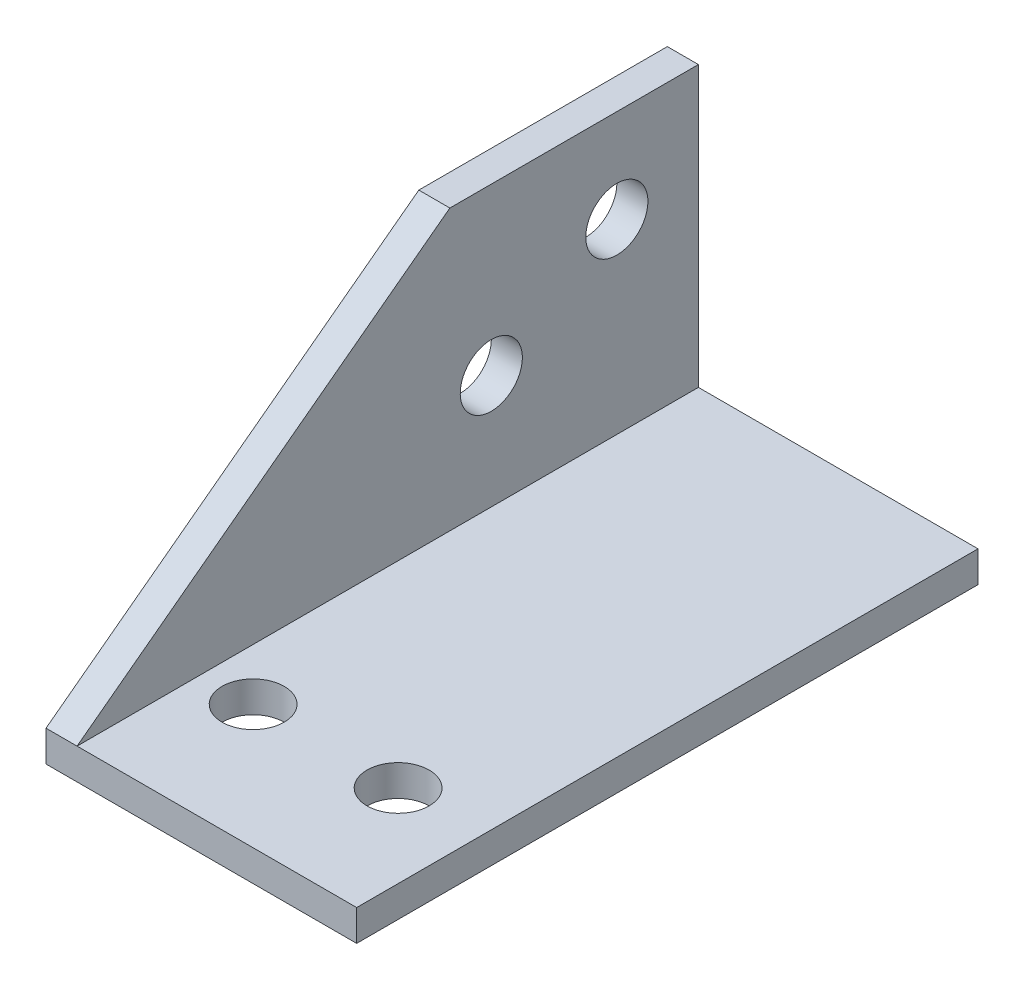
SolidWorks part; units mm, degrees
ref_plane "Plan de face" through (0, 0, 0) normal (0, 0, 1) x (1, 0, 0)
ref_plane "Plan de dessus" through (0, 0, 0) normal (0, 1, 0) x (1, 0, 0)
ref_plane "Plan de droite" through (0, 0, 0) normal (1, 0, 0) x (0, 0, -1)
sketch "Esquisse1" plane through (0, 0, 0) normal (0, 0, 1) x (1, 0, 0)
  line L0 (-13.9999, 0.6824) -> (-15.4999, 0.6824)
  line L1 (-15.4999, 0.6824) -> (-15.4999, -14.3176)
  line L2 (-15.4999, -14.3176) -> (-0.4999, -14.3176)
  line L3 (-0.4999, -14.3176) -> (-0.4999, -12.8176)
  line L4 (-0.4999, -12.8176) -> (-13.9999, -12.8176)
  line L5 (-13.9999, -12.8176) -> (-13.9999, 0.6824)
  dimension "D1" = 1.5
  dimension "D2" = 1.5
  dimension "D3" = 15
  dimension "D4" = 15
extrude "Extrusion1" add sketch "Esquisse1" along normal blind 30
sketch "Esquisse2" plane through (0, -12.8176, 0) normal (0, 1, 0) x (-1, 0, 0)
  line L0 (0.4999, 30) -> (0.4999, 0) construction
  line L1 (0.4999, 30) -> (13.9999, 30) construction
  circle A0 centre (4.4999, 24) radius 1.5
  circle A1 centre (11.4999, 24) radius 1.5
  dimension "D1" = 7
  dimension "D2" = 4
  dimension "D3" = 6
  dimension "D4" = 6
extrude "Extrusion2" cut sketch "Esquisse2" against normal blind 50
sketch "Esquisse3" plane through (-13.9999, 0, 0) normal (1, 0, 0) x (0, 0, -1)
  line L0 (-30, 0.6824) -> (0, 0.6824) construction
  line L1 (0, -12.8176) -> (0, 0.6824) construction
  line L2 (-30, 0.6824) -> (-30, -12.8176)
  line L3 (-30, -12.8176) -> (-12, 0.6824)
  line L4 (-12, 0.6824) -> (-30, 0.6824)
  circle A0 centre (-10, -7.3176) radius 1.5
  circle A1 centre (-10, -7.3176) radius 7 construction
  circle A2 centre (-3.9378, -3.8176) radius 1.5
  dimension "D1" = 8
  dimension "D3" = 14
  dimension "D4" = 4.5
  dimension "D5" = 18
  dimension "D2" = 10
extrude "Extrusion3" cut sketch "Esquisse3" against normal blind 50
